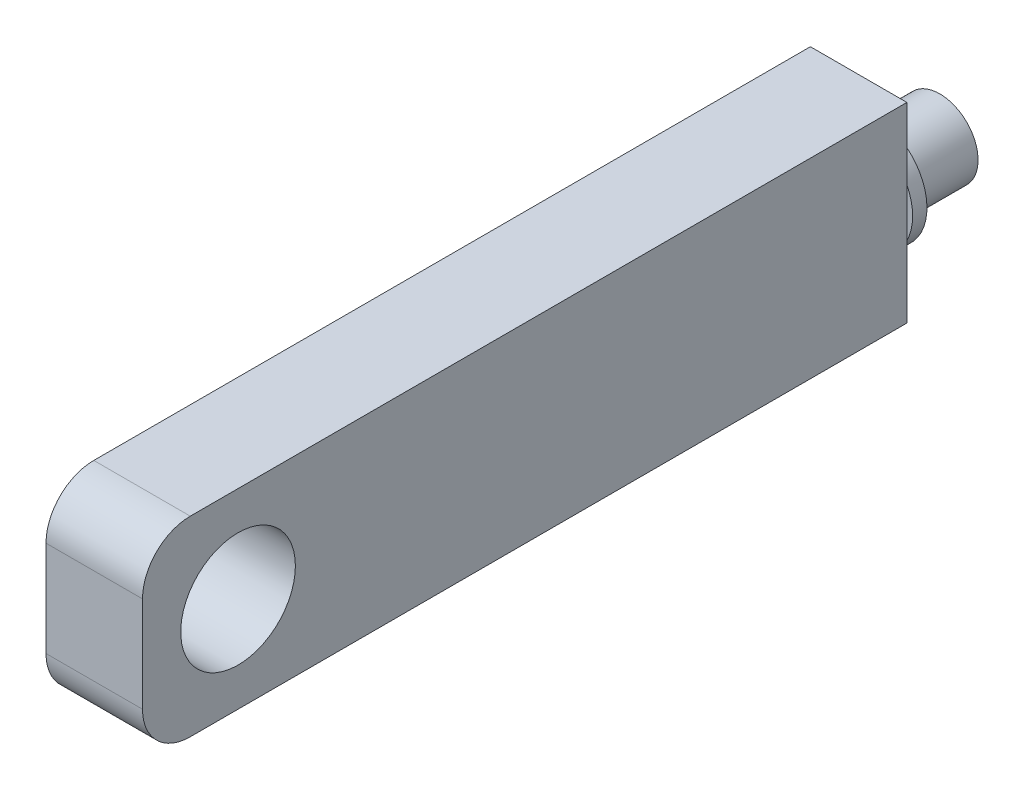
SolidWorks part; units mm, degrees
ref_plane "Front Plane" through (0, 0, 0) normal (0, 0, 1) x (1, 0, 0)
ref_plane "Top Plane" through (0, 0, 0) normal (0, 1, 0) x (1, 0, 0)
ref_plane "Right Plane" through (0, 0, 0) normal (1, 0, 0) x (0, 0, -1)
sketch "Sketch1" plane through (0, 0, 0) normal (0, 1, 0) x (1, 0, 0)
  line L0 (0, 0) -> (10.1, 0)
  line L1 (10.1, 0) -> (10.1, 80)
  line L2 (0, 0) -> (0, 80)
  line L3 (0, 80) -> (10.1, 80)
  dimension "D1" = 10.1
  dimension "D2" = 80
  dimension "D3" = 80
extrude "Boss-Extrude1" add sketch "Sketch1" along normal blind 20
sketch "Sketch2" plane through (10.1, 0, 0) normal (1, 0, 0) x (0, 0, -1)
  line L0 (0, 20) -> (0, 0) construction
  circle A0 centre (10, 10) radius 6
  dimension "D1" = 10
  dimension "D2" = 10
extrude "Cut-Extrude1" cut sketch "Sketch2" against normal up to next
fillet "Fillet1" radius 5 2 edges at (5.05, 0, 0) (5.05, 20, 0)
sketch "Sketch3" plane through (0, 0, -80) normal (0, 0, -1) x (-1, 0, 0)
  line L1 (0, 0) -> (-10.1, 0) construction
  circle A0 centre (-5.05, 10) radius 4
  dimension "D1" = 5.05
  dimension "D2" = 10
extrude "Boss-Extrude2" add sketch "Sketch3" along normal blind 8.5
sketch "Sketch4" plane through (0, 0, -80) normal (0, 0, -1) x (-1, 0, 0)
  line L0 (-5.05, 6) -> (-5.05, 10) construction
  circle A0 centre (-5.05, 10) radius 5.65
  circle A1 centre (-5.05, 10) radius 4 construction
  dimension "D1" = 0
  dimension "D3" = 11.3
  dimension "D2" = 0
extrude "Boss-Extrude3" add sketch "Sketch4" along normal blind 1.5
